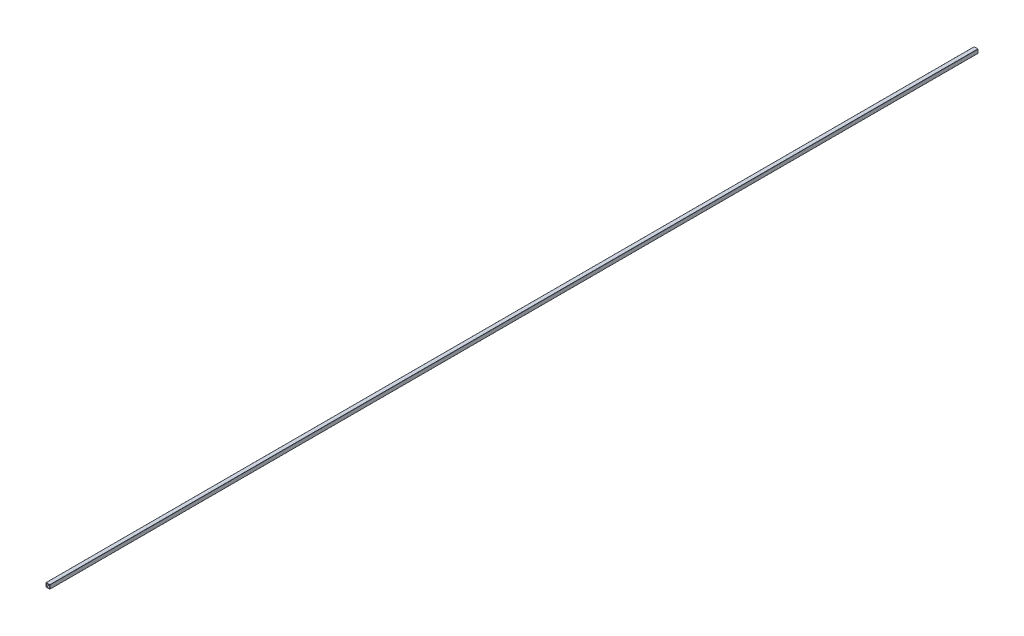
SolidWorks part; units mm, degrees
material "AISI 1035 Acero (SS)"
ref_plane "Alzado" through (0, 0, 0) normal (0, 0, 1) x (1, 0, 0)
ref_plane "Planta" through (0, 0, 0) normal (0, 1, 0) x (1, 0, 0)
ref_plane "Vista lateral" through (0, 0, 0) normal (1, 0, 0) x (0, 0, -1)
sketch "Croquis1" plane through (0, 0, 0) normal (0, 0, 1) x (1, 0, 0)
  line L0 (-10.04, -10.04) -> (-10.04, 10.04)
  line L1 (-11.7, -12.7) -> (11.7, -12.7)
  line L2 (-12.7, -11.7) -> (-12.7, 11.7)
  line L3 (-11.7, 12.7) -> (11.7, 12.7)
  line L4 (12.7, -11.7) -> (12.7, 11.7)
  line L5 (-12.7, -12.7) -> (12.7, 12.7) construction
  line L6 (-12.7, 12.7) -> (12.7, -12.7) construction
  line L7 (-10.04, 10.04) -> (10.04, 10.04)
  line L8 (10.04, -10.04) -> (10.04, 10.04)
  line L9 (-10.04, -10.04) -> (10.04, -10.04)
  line L10 (-12.7, 12.7) -> (12.7, 12.7) construction
  line L11 (12.7, -12.7) -> (12.7, 12.7) construction
  line L12 (-12.7, -12.7) -> (12.7, -12.7) construction
  line L13 (-12.7, -12.7) -> (-12.7, 12.7) construction
  arc A0 (11.7, 12.7) -> (12.7, 11.7) centre (11.7, 11.7) cw
  arc A1 (11.7, -12.7) -> (12.7, -11.7) centre (11.7, -11.7) ccw
  arc A2 (-11.7, -12.7) -> (-12.7, -11.7) centre (-11.7, -11.7) cw
  arc A3 (-12.7, 11.7) -> (-11.7, 12.7) centre (-11.7, 11.7) cw
  point P0 (0, 0)
  dimension "D4" = 1
  dimension "D1" = 25.4
  dimension "D2" = 25.4
  dimension "D3" = 2.66
extrude "Saliente-Extruir1" add sketch "Croquis1" along normal blind 6000
